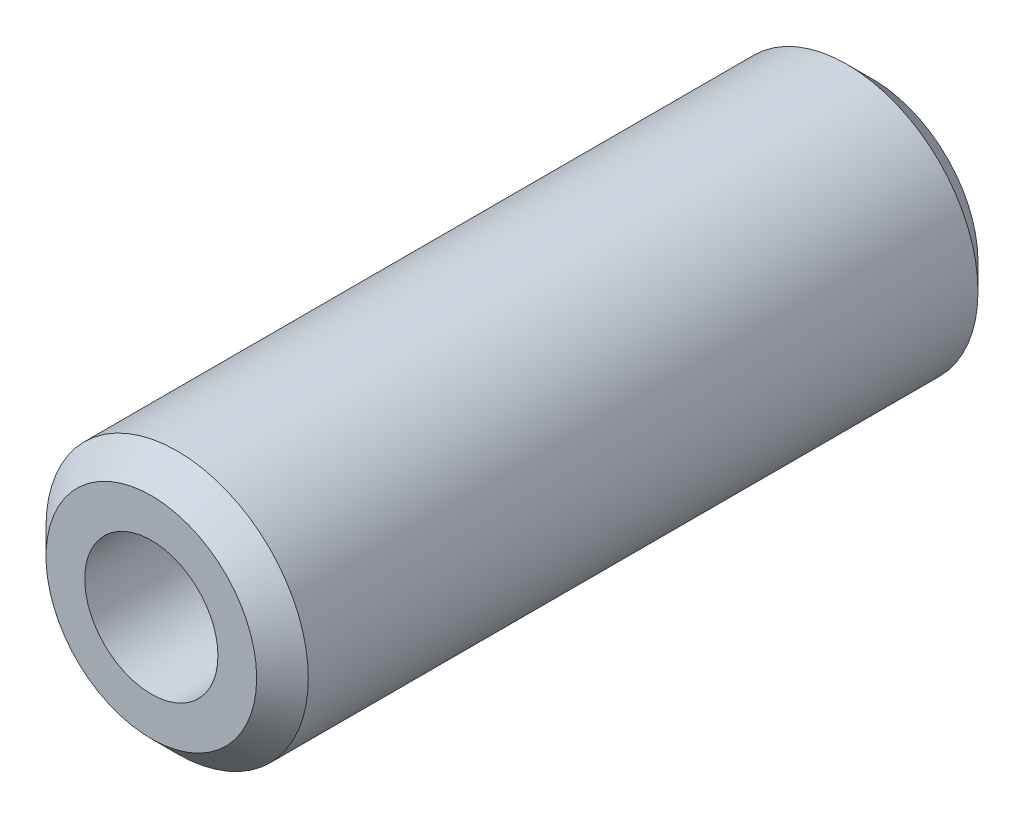
SolidWorks part; units mm, degrees
ref_plane "Front Plane" through (0, 0, 0) normal (0, 0, 1) x (1, 0, 0)
ref_plane "Top Plane" through (0, 0, 0) normal (0, 1, 0) x (1, 0, 0)
ref_plane "Right Plane" through (0, 0, 0) normal (1, 0, 0) x (0, 0, -1)
sketch "Sketch1" plane through (0, 0, 0) normal (0, 0, 1) x (1, 0, 0)
  circle A0 centre (0, 0) radius 12.7
  dimension "D1" = 25.4
extrude "Boss-Extrude1" add sketch "Sketch1" along normal blind 69.85
sketch "Sketch2" plane through (0, 0, 69.85) normal (0, 0, 1) x (1, 0, 0)
  circle A0 centre (0, 0) radius 6.45
  dimension "D1" = 12.9
extrude "Cut-Extrude1" cut sketch "Sketch2" against normal through all
chamfer "Chamfer1" distance 2.5 angle 45 2 edges at (12.7, 0, 0) (12.7, 0, 69.85)
